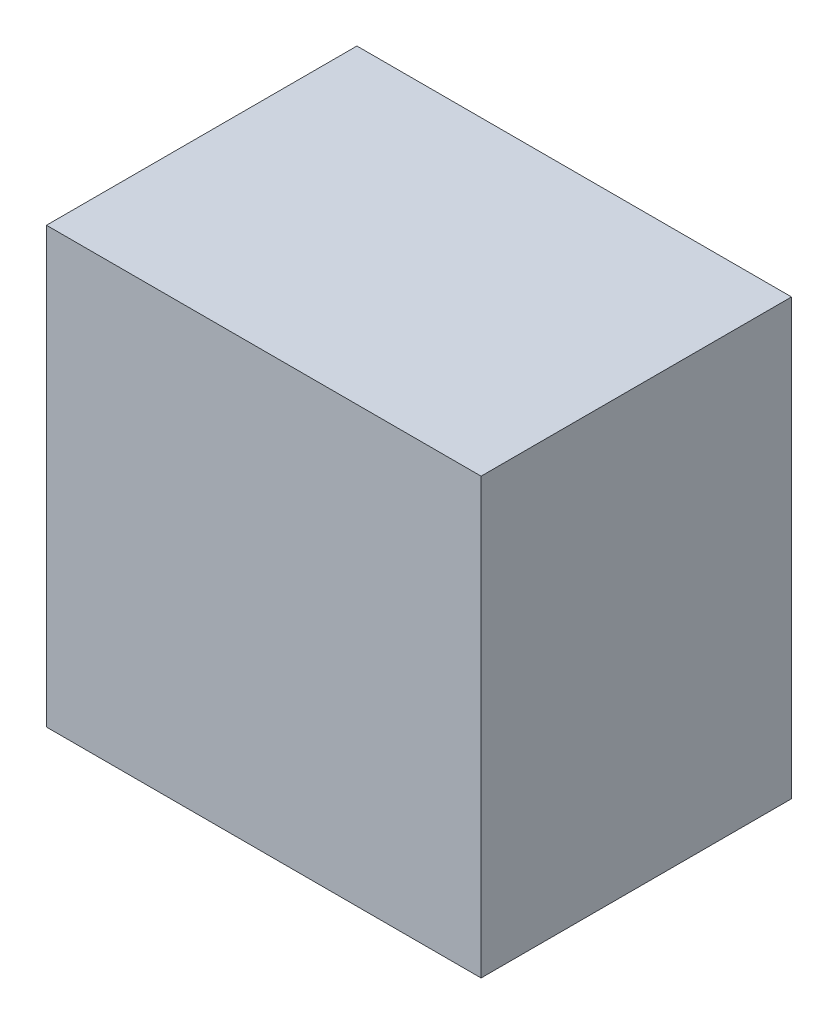
SolidWorks part; units mm, degrees
ref_plane "Front Plane" through (0, 0, 0) normal (0, 0, 1) x (1, 0, 0)
ref_plane "Top Plane" through (0, 0, 0) normal (0, 1, 0) x (1, 0, 0)
ref_plane "Right Plane" through (0, 0, 0) normal (1, 0, 0) x (0, 0, -1)
other "Configuration Table"
sketch "Sketch1" plane through (0, 0, 0) normal (0, 0, 1) x (1, 0, 0)
  line L1 (-28, 40) -> (28, 40)
  line L2 (-28, 40) -> (-28, 96)
  line L3 (-28, 96) -> (28, 96)
  line L4 (28, 40) -> (28, 96)
extrude "SM_motor_helezon_57x57x40_1" add sketch "Sketch1" against normal blind 40 from offset 740 separate body
